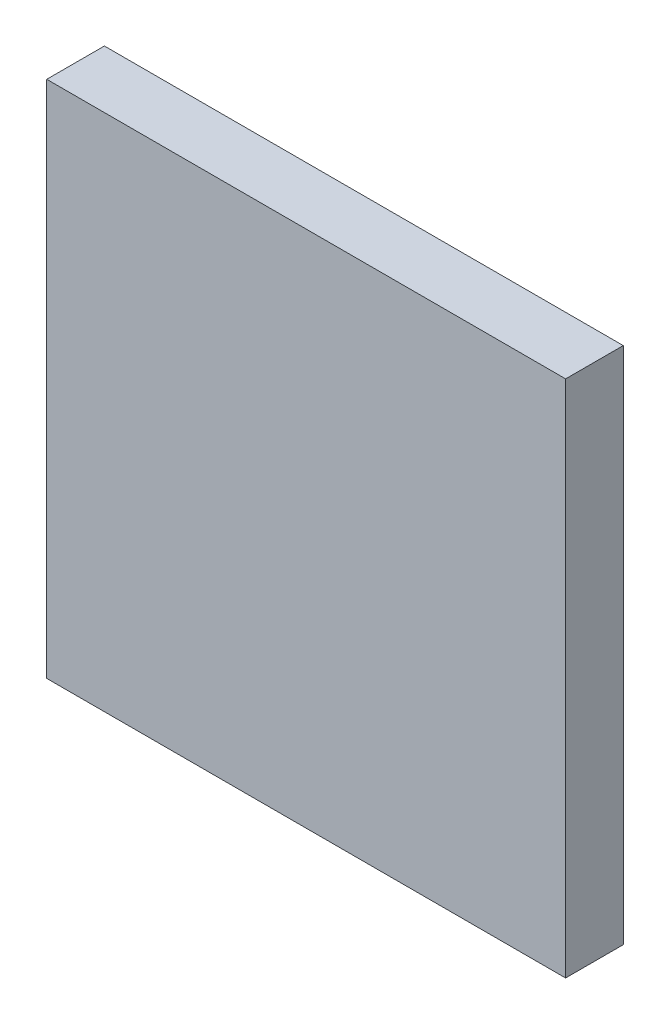
SolidWorks part; units mm, degrees
ref_plane "Спереди" through (0, 0, 0) normal (0, 0, 1) x (1, 0, 0)
ref_plane "Сверху" through (0, 0, 0) normal (0, 1, 0) x (1, 0, 0)
ref_plane "Справа" through (0, 0, 0) normal (1, 0, 0) x (0, 0, -1)
sketch "Эскиз1" plane through (0, 0, 0) normal (0, 0, 1) x (1, 0, 0)
  line L1 (-13.5, 13.5) -> (13.5, 13.5)
  line L2 (-13.5, 13.5) -> (-13.5, -13.5)
  line L3 (-13.5, -13.5) -> (13.5, -13.5)
  line L4 (13.5, 13.5) -> (13.5, -13.5)
  line L5 (-13.5, 13.5) -> (13.5, -13.5) construction
  line L6 (-13.5, -13.5) -> (13.5, 13.5) construction
  point P0 (0, 0)
  dimension "D1" = 27
  dimension "D2" = 27
extrude "Бобышка-Вытянуть1" add sketch "Эскиз1" along normal blind 3
sketch "Эскиз2" plane through (0, 0, 0) normal (0, 0, -1) x (-1, 0, 0)
  line L0 (0, 0) -> (13.5, 0) construction
  line L1 (13.5, 13.5) -> (13.5, -13.5) construction
  line L2 (0, 0) -> (0, -13.5) construction
  line L3 (13.5, -13.5) -> (-13.5, -13.5) construction
  line L4 (-0.5, -0.5) -> (-1.5, -0.5)
  line L5 (0.5, -1.5) -> (-0.5, -1.5)
  line L6 (0.5, -1.5) -> (0.5, -0.5)
  line L7 (0.5, 1.5) -> (-0.5, 1.5)
  line L8 (-0.5, -1.5) -> (-0.5, -0.5)
  line L9 (0.5, -1.5) -> (-0.5, 1.5) construction
  line L10 (0.5, 1.5) -> (-0.5, -1.5) construction
  line L11 (1.5, -0.5) -> (0.5, -0.5)
  line L12 (1.5, -0.5) -> (1.5, 0.5)
  line L13 (1.5, 0.5) -> (0.5, 0.5)
  line L14 (-1.5, -0.5) -> (-1.5, 0.5)
  line L15 (1.5, -0.5) -> (-1.5, 0.5) construction
  line L16 (1.5, 0.5) -> (-1.5, -0.5) construction
  line L17 (0.5, 0.5) -> (0.5, 1.5)
  line L18 (-0.5, 0.5) -> (-1.5, 0.5)
  line L19 (-0.5, 0.5) -> (-0.5, 1.5)
  line L20 (0, -9) -> (3.8771, -9) construction
  line L21 (1.5, 8.5) -> (-1.5, 9.5) construction
  line L22 (-0.5, -9.5) -> (-1.5, -9.5)
  line L23 (0.5, -10.5) -> (-0.5, -10.5)
  line L24 (0.5, -10.5) -> (0.5, -9.5)
  line L25 (0.5, -7.5) -> (-0.5, -7.5)
  line L26 (-0.5, -10.5) -> (-0.5, -9.5)
  line L27 (0.5, -10.5) -> (-0.5, -7.5) construction
  line L28 (0.5, -7.5) -> (-0.5, -10.5) construction
  line L29 (1.5, -9.5) -> (0.5, -9.5)
  line L30 (1.5, -9.5) -> (1.5, -8.5)
  line L31 (1.5, -8.5) -> (0.5, -8.5)
  line L32 (-1.5, -9.5) -> (-1.5, -8.5)
  line L33 (1.5, -9.5) -> (-1.5, -8.5) construction
  line L34 (1.5, -8.5) -> (-1.5, -9.5) construction
  line L35 (0.5, -8.5) -> (0.5, -7.5)
  line L36 (-0.5, -8.5) -> (-1.5, -8.5)
  line L37 (-0.5, -8.5) -> (-0.5, -7.5)
  line L38 (1.5, 9.5) -> (-1.5, 8.5) construction
  line L39 (0.5, 7.5) -> (-0.5, 10.5) construction
  line L40 (0.5, 10.5) -> (-0.5, 7.5) construction
  line L41 (-0.5, 8.5) -> (-0.5, 7.5)
  line L42 (-0.5, 8.5) -> (-1.5, 8.5)
  line L43 (0.5, 8.5) -> (0.5, 7.5)
  line L44 (-1.5, 9.5) -> (-1.5, 8.5)
  line L45 (1.5, 8.5) -> (0.5, 8.5)
  line L46 (1.5, 9.5) -> (1.5, 8.5)
  line L47 (1.5, 9.5) -> (0.5, 9.5)
  line L48 (-0.5, 10.5) -> (-0.5, 9.5)
  line L49 (0.5, 7.5) -> (-0.5, 7.5)
  line L50 (0.5, 10.5) -> (0.5, 9.5)
  line L51 (0.5, 10.5) -> (-0.5, 10.5)
  line L52 (-0.5, 9.5) -> (-1.5, 9.5)
  line L53 (2.5, -0.5) -> (5.5, -0.5)
  line L54 (5.5, -0.5) -> (5.5, -1.5)
  line L55 (5.5, -1.5) -> (6.5, -1.5)
  line L56 (6.5, -1.5) -> (6.5, -2.5)
  line L57 (6.5, -2.5) -> (7.5, -2.5)
  line L58 (7.5, -2.5) -> (7.5, -3.5)
  line L59 (7.5, -3.5) -> (8.5, -3.5)
  line L60 (8.5, -3.5) -> (8.5, -4.5)
  line L61 (8.5, -4.5) -> (5.5, -4.5)
  line L62 (5.5, -4.5) -> (5.5, -3.5)
  line L63 (5.5, -3.5) -> (4.5, -3.5)
  line L64 (4.5, -3.5) -> (4.5, -2.5)
  line L65 (4.5, -2.5) -> (3.5, -2.5)
  line L66 (3.5, -2.5) -> (3.5, -1.5)
  line L67 (3.5, -1.5) -> (2.5, -1.5)
  line L68 (2.5, -1.5) -> (2.5, -0.5)
  line L69 (5.5, -1.5) -> (5.5, -3.5) construction
  line L70 (5.5, -10.5) -> (5.5, -5.5)
  line L71 (5.5, -5.5) -> (10.5, -5.5)
  line L72 (10.5, -5.5) -> (10.5, -6.5)
  line L73 (10.5, -6.5) -> (6.5, -6.5)
  line L74 (6.5, -6.5) -> (6.5, -10.5)
  line L75 (6.5, -10.5) -> (5.5, -10.5)
  line L76 (5.5, -4.5) -> (5.5, -5.5) construction
  line L77 (8.5, -12.5) -> (7.5, -12.5)
  line L78 (7.5, -12.5) -> (7.5, -7.5)
  line L79 (7.5, -7.5) -> (12.5, -7.5)
  line L80 (12.5, -7.5) -> (12.5, -8.5)
  line L81 (12.5, -8.5) -> (8.5, -8.5)
  line L82 (8.5, -8.5) -> (8.5, -12.5)
  line L83 (9.5, -12.5) -> (9.5, -10.5)
  line L84 (9.5, -10.5) -> (10.5, -10.5)
  line L85 (10.5, -10.5) -> (10.5, -9.5)
  line L86 (10.5, -9.5) -> (12.5, -9.5)
  line L87 (12.5, -9.5) -> (12.5, -10.5)
  line L88 (12.5, -10.5) -> (11.5, -10.5)
  line L89 (11.5, -10.5) -> (11.5, -11.5)
  line L90 (11.5, -11.5) -> (10.5, -11.5)
  line L91 (10.5, -11.5) -> (10.5, -12.5)
  line L92 (10.5, -12.5) -> (9.5, -12.5)
  line L93 (0.5, -2.5) -> (0.5, -6.5)
  line L94 (0.5, -6.5) -> (1.5, -6.5)
  line L95 (1.5, -6.5) -> (1.5, -7.5)
  line L96 (1.5, -7.5) -> (2.5, -7.5)
  line L97 (2.5, -7.5) -> (2.5, -8.5)
  line L98 (2.5, -8.5) -> (3.5, -8.5)
  line L99 (3.5, -8.5) -> (3.5, -9.5)
  line L100 (3.5, -9.5) -> (4.5, -9.5)
  line L103 (4.5, -9.5) -> (4.5, -5.5)
  line L106 (4.5, -5.5) -> (3.5, -5.5)
  line L107 (3.5, -5.5) -> (3.5, -4.5)
  line L108 (3.5, -4.5) -> (2.5, -4.5)
  line L109 (2.5, -4.5) -> (2.5, -3.5)
  line L110 (2.5, -3.5) -> (1.5, -3.5)
  line L111 (1.5, -3.5) -> (1.5, -2.5)
  line L112 (1.5, -2.5) -> (0.5, -2.5)
  line L113 (0.5, -6.5) -> (0.5, -7.5) construction
  line L114 (1.5, -3.5) -> (1.5, -6.5) construction
  line L115 (2.5, -4.5) -> (2.5, -7.5) construction
  line L116 (0.5, -10.5) -> (0.5, -11.5) construction
  line L117 (4.5, -12.5) -> (0.5, -12.5)
  line L118 (4.5, -12.5) -> (4.5, -11.5)
  line L119 (4.5, -11.5) -> (0.5, -11.5)
  line L120 (0.5, -12.5) -> (0.5, -11.5)
  line L121 (9, 0) -> (17.8062, 0) construction
  line L122 (9, 0) -> (9, -6.8908) construction
  line L123 (8.5, -0.5) -> (7.5, -0.5)
  line L124 (9.5, -1.5) -> (8.5, -1.5)
  line L125 (9.5, -1.5) -> (9.5, -0.5)
  line L126 (9.5, 1.5) -> (8.5, 1.5)
  line L127 (8.5, -1.5) -> (8.5, -0.5)
  line L128 (9.5, -1.5) -> (8.5, 1.5) construction
  line L129 (9.5, 1.5) -> (8.5, -1.5) construction
  line L130 (10.5, -0.5) -> (9.5, -0.5)
  line L131 (10.5, -0.5) -> (10.5, 0.5)
  line L132 (10.5, 0.5) -> (9.5, 0.5)
  line L133 (7.5, -0.5) -> (7.5, 0.5)
  line L134 (10.5, -0.5) -> (7.5, 0.5) construction
  line L135 (10.5, 0.5) -> (7.5, -0.5) construction
  line L136 (9.5, 0.5) -> (9.5, 1.5)
  line L137 (8.5, 0.5) -> (7.5, 0.5)
  line L138 (8.5, 0.5) -> (8.5, 1.5)
  line L139 (-9, 0) -> (0, 0) construction
  line L140 (-9, 0) -> (-9, -7.0023) construction
  line L141 (-9.5, -0.5) -> (-10.5, -0.5)
  line L142 (-8.5, -1.5) -> (-9.5, -1.5)
  line L143 (-8.5, -1.5) -> (-8.5, -0.5)
  line L144 (-8.5, 1.5) -> (-9.5, 1.5)
  line L145 (-9.5, -1.5) -> (-9.5, -0.5)
  line L146 (-8.5, -1.5) -> (-9.5, 1.5) construction
  line L147 (-8.5, 1.5) -> (-9.5, -1.5) construction
  line L148 (-7.5, -0.5) -> (-8.5, -0.5)
  line L149 (-7.5, -0.5) -> (-7.5, 0.5)
  line L150 (-7.5, 0.5) -> (-8.5, 0.5)
  line L151 (-10.5, -0.5) -> (-10.5, 0.5)
  line L152 (-7.5, -0.5) -> (-10.5, 0.5) construction
  line L153 (-7.5, 0.5) -> (-10.5, -0.5) construction
  line L154 (-8.5, 0.5) -> (-8.5, 1.5)
  line L155 (-9.5, 0.5) -> (-10.5, 0.5)
  line L156 (-9.5, 0.5) -> (-9.5, 1.5)
  line L157 (-4.5, -11.5) -> (-0.5, -11.5)
  line L158 (-0.5, -12.5) -> (-0.5, -11.5)
  line L159 (-4.5, -12.5) -> (-0.5, -12.5)
  line L160 (-4.5, -12.5) -> (-4.5, -11.5)
  line L161 (-10.5, -12.5) -> (-9.5, -12.5)
  line L162 (-10.5, -11.5) -> (-10.5, -12.5)
  line L163 (-11.5, -11.5) -> (-10.5, -11.5)
  line L164 (-11.5, -10.5) -> (-11.5, -11.5)
  line L165 (-12.5, -10.5) -> (-11.5, -10.5)
  line L166 (-12.5, -9.5) -> (-12.5, -10.5)
  line L167 (-10.5, -9.5) -> (-12.5, -9.5)
  line L168 (-10.5, -10.5) -> (-10.5, -9.5)
  line L169 (-9.5, -10.5) -> (-10.5, -10.5)
  line L170 (-9.5, -12.5) -> (-9.5, -10.5)
  line L171 (-12.5, -8.5) -> (-8.5, -8.5)
  line L172 (-12.5, -7.5) -> (-12.5, -8.5)
  line L173 (-7.5, -7.5) -> (-12.5, -7.5)
  line L174 (-7.5, -12.5) -> (-7.5, -7.5)
  line L175 (-8.5, -12.5) -> (-7.5, -12.5)
  line L176 (-8.5, -8.5) -> (-8.5, -12.5)
  line L177 (-6.5, -6.5) -> (-6.5, -10.5)
  line L178 (-10.5, -6.5) -> (-6.5, -6.5)
  line L179 (-10.5, -5.5) -> (-10.5, -6.5)
  line L180 (-5.5, -5.5) -> (-10.5, -5.5)
  line L181 (-5.5, -10.5) -> (-5.5, -5.5)
  line L182 (-6.5, -10.5) -> (-5.5, -10.5)
  line L183 (-3.5, -1.5) -> (-2.5, -1.5)
  line L184 (-3.5, -2.5) -> (-3.5, -1.5)
  line L185 (-4.5, -2.5) -> (-3.5, -2.5)
  line L186 (-4.5, -3.5) -> (-4.5, -2.5)
  line L187 (-5.5, -3.5) -> (-4.5, -3.5)
  line L188 (-5.5, -4.5) -> (-5.5, -3.5)
  line L189 (-8.5, -4.5) -> (-5.5, -4.5)
  line L190 (-8.5, -3.5) -> (-8.5, -4.5)
  line L191 (-7.5, -3.5) -> (-8.5, -3.5)
  line L192 (-7.5, -2.5) -> (-7.5, -3.5)
  line L193 (-6.5, -2.5) -> (-7.5, -2.5)
  line L194 (-6.5, -1.5) -> (-6.5, -2.5)
  line L195 (-5.5, -1.5) -> (-6.5, -1.5)
  line L196 (-5.5, -0.5) -> (-5.5, -1.5)
  line L197 (-2.5, -0.5) -> (-5.5, -0.5)
  line L198 (-2.5, -1.5) -> (-2.5, -0.5)
  line L199 (-3.5, -9.5) -> (-4.5, -9.5)
  line L200 (-3.5, -8.5) -> (-3.5, -9.5)
  line L201 (-2.5, -8.5) -> (-3.5, -8.5)
  line L202 (-2.5, -7.5) -> (-2.5, -8.5)
  line L203 (-1.5, -7.5) -> (-2.5, -7.5)
  line L204 (-1.5, -6.5) -> (-1.5, -7.5)
  line L205 (-0.5, -6.5) -> (-1.5, -6.5)
  line L206 (-0.5, -2.5) -> (-0.5, -6.5)
  line L207 (-1.5, -2.5) -> (-0.5, -2.5)
  line L208 (-1.5, -3.5) -> (-1.5, -2.5)
  line L209 (-2.5, -3.5) -> (-1.5, -3.5)
  line L210 (-2.5, -4.5) -> (-2.5, -3.5)
  line L211 (-3.5, -4.5) -> (-2.5, -4.5)
  line L212 (-3.5, -5.5) -> (-3.5, -4.5)
  line L213 (-4.5, -5.5) -> (-3.5, -5.5)
  line L214 (-4.5, -9.5) -> (-4.5, -5.5)
  line L215 (8.5, -4.5) -> (11.5, -4.5) construction
  line L216 (12.5, -0.5) -> (11.5, -0.5)
  line L217 (12.5, -0.5) -> (12.5, -4.5)
  line L218 (12.5, -4.5) -> (11.5, -4.5)
  line L219 (11.5, -0.5) -> (11.5, -4.5)
  line L220 (12.5, -4.5) -> (12.5, -7.5) construction
  line L221 (-12.5, -4.5) -> (-11.5, -4.5)
  line L222 (-11.5, -0.5) -> (-11.5, -4.5)
  line L223 (-12.5, -0.5) -> (-11.5, -0.5)
  line L224 (-12.5, -0.5) -> (-12.5, -4.5)
  line L225 (-10.5, 11.5) -> (-10.5, 12.5)
  line L226 (-11.5, 11.5) -> (-10.5, 11.5)
  line L227 (-11.5, 10.5) -> (-11.5, 11.5)
  line L228 (-12.5, 10.5) -> (-11.5, 10.5)
  line L229 (-12.5, 9.5) -> (-12.5, 10.5)
  line L230 (-10.5, 9.5) -> (-12.5, 9.5)
  line L231 (-10.5, 10.5) -> (-10.5, 9.5)
  line L232 (-9.5, 10.5) -> (-10.5, 10.5)
  line L233 (-9.5, 12.5) -> (-9.5, 10.5)
  line L234 (-10.5, 12.5) -> (-9.5, 12.5)
  line L235 (-12.5, 7.5) -> (-12.5, 8.5)
  line L236 (-7.5, 7.5) -> (-12.5, 7.5)
  line L237 (-7.5, 12.5) -> (-7.5, 7.5)
  line L238 (-8.5, 12.5) -> (-7.5, 12.5)
  line L239 (-8.5, 8.5) -> (-8.5, 12.5)
  line L240 (-12.5, 8.5) -> (-8.5, 8.5)
  line L241 (-10.5, 6.5) -> (-6.5, 6.5)
  line L242 (-10.5, 5.5) -> (-10.5, 6.5)
  line L243 (-5.5, 5.5) -> (-10.5, 5.5)
  line L244 (-5.5, 10.5) -> (-5.5, 5.5)
  line L245 (-6.5, 10.5) -> (-5.5, 10.5)
  line L246 (-6.5, 6.5) -> (-6.5, 10.5)
  line L247 (-12.5, 0.5) -> (-12.5, 4.5)
  line L248 (-12.5, 0.5) -> (-11.5, 0.5)
  line L249 (-11.5, 0.5) -> (-11.5, 4.5)
  line L250 (-12.5, 4.5) -> (-11.5, 4.5)
  line L251 (-3.5, 2.5) -> (-3.5, 1.5)
  line L252 (-4.5, 2.5) -> (-3.5, 2.5)
  line L253 (-4.5, 3.5) -> (-4.5, 2.5)
  line L254 (-5.5, 3.5) -> (-4.5, 3.5)
  line L255 (-5.5, 4.5) -> (-5.5, 3.5)
  line L256 (-8.5, 4.5) -> (-5.5, 4.5)
  line L257 (-8.5, 3.5) -> (-8.5, 4.5)
  line L258 (-7.5, 3.5) -> (-8.5, 3.5)
  line L259 (-7.5, 2.5) -> (-7.5, 3.5)
  line L260 (-6.5, 2.5) -> (-7.5, 2.5)
  line L261 (-6.5, 1.5) -> (-6.5, 2.5)
  line L262 (-5.5, 1.5) -> (-6.5, 1.5)
  line L263 (-5.5, 0.5) -> (-5.5, 1.5)
  line L264 (-2.5, 0.5) -> (-5.5, 0.5)
  line L265 (-2.5, 1.5) -> (-2.5, 0.5)
  line L266 (-3.5, 1.5) -> (-2.5, 1.5)
  line L267 (-3.5, 8.5) -> (-3.5, 9.5)
  line L268 (-2.5, 8.5) -> (-3.5, 8.5)
  line L269 (-2.5, 7.5) -> (-2.5, 8.5)
  line L270 (-1.5, 7.5) -> (-2.5, 7.5)
  line L271 (-1.5, 6.5) -> (-1.5, 7.5)
  line L272 (-0.5, 6.5) -> (-1.5, 6.5)
  line L273 (-0.5, 2.5) -> (-0.5, 6.5)
  line L274 (-1.5, 2.5) -> (-0.5, 2.5)
  line L275 (-1.5, 3.5) -> (-1.5, 2.5)
  line L276 (-2.5, 3.5) -> (-1.5, 3.5)
  line L277 (-2.5, 4.5) -> (-2.5, 3.5)
  line L278 (-3.5, 4.5) -> (-2.5, 4.5)
  line L279 (-3.5, 5.5) -> (-3.5, 4.5)
  line L280 (-4.5, 5.5) -> (-3.5, 5.5)
  line L281 (-4.5, 9.5) -> (-4.5, 5.5)
  line L282 (-3.5, 9.5) -> (-4.5, 9.5)
  line L283 (-4.5, 12.5) -> (-4.5, 11.5)
  line L284 (-4.5, 12.5) -> (-0.5, 12.5)
  line L285 (-0.5, 12.5) -> (-0.5, 11.5)
  line L286 (-4.5, 11.5) -> (-0.5, 11.5)
  line L287 (4.5, 11.5) -> (0.5, 11.5)
  line L288 (0.5, 12.5) -> (0.5, 11.5)
  line L289 (4.5, 12.5) -> (0.5, 12.5)
  line L290 (4.5, 12.5) -> (4.5, 11.5)
  line L291 (3.5, 9.5) -> (4.5, 9.5)
  line L292 (3.5, 8.5) -> (3.5, 9.5)
  line L293 (2.5, 8.5) -> (3.5, 8.5)
  line L294 (2.5, 7.5) -> (2.5, 8.5)
  line L295 (1.5, 7.5) -> (2.5, 7.5)
  line L296 (1.5, 6.5) -> (1.5, 7.5)
  line L297 (0.5, 6.5) -> (1.5, 6.5)
  line L298 (0.5, 2.5) -> (0.5, 6.5)
  line L299 (1.5, 2.5) -> (0.5, 2.5)
  line L300 (1.5, 3.5) -> (1.5, 2.5)
  line L301 (2.5, 3.5) -> (1.5, 3.5)
  line L302 (2.5, 4.5) -> (2.5, 3.5)
  line L303 (3.5, 4.5) -> (2.5, 4.5)
  line L304 (3.5, 5.5) -> (3.5, 4.5)
  line L305 (4.5, 5.5) -> (3.5, 5.5)
  line L306 (4.5, 9.5) -> (4.5, 5.5)
  line L307 (10.5, 12.5) -> (9.5, 12.5)
  line L308 (10.5, 11.5) -> (10.5, 12.5)
  line L309 (11.5, 11.5) -> (10.5, 11.5)
  line L310 (11.5, 10.5) -> (11.5, 11.5)
  line L311 (12.5, 10.5) -> (11.5, 10.5)
  line L312 (12.5, 9.5) -> (12.5, 10.5)
  line L313 (10.5, 9.5) -> (12.5, 9.5)
  line L314 (10.5, 10.5) -> (10.5, 9.5)
  line L315 (9.5, 10.5) -> (10.5, 10.5)
  line L316 (9.5, 12.5) -> (9.5, 10.5)
  line L317 (12.5, 8.5) -> (8.5, 8.5)
  line L318 (12.5, 7.5) -> (12.5, 8.5)
  line L319 (7.5, 7.5) -> (12.5, 7.5)
  line L320 (7.5, 12.5) -> (7.5, 7.5)
  line L321 (8.5, 12.5) -> (7.5, 12.5)
  line L322 (8.5, 8.5) -> (8.5, 12.5)
  line L323 (6.5, 6.5) -> (6.5, 10.5)
  line L324 (10.5, 6.5) -> (6.5, 6.5)
  line L325 (10.5, 5.5) -> (10.5, 6.5)
  line L326 (5.5, 5.5) -> (10.5, 5.5)
  line L327 (5.5, 10.5) -> (5.5, 5.5)
  line L328 (6.5, 10.5) -> (5.5, 10.5)
  line L329 (3.5, 1.5) -> (2.5, 1.5)
  line L330 (3.5, 2.5) -> (3.5, 1.5)
  line L331 (4.5, 2.5) -> (3.5, 2.5)
  line L332 (4.5, 3.5) -> (4.5, 2.5)
  line L333 (5.5, 3.5) -> (4.5, 3.5)
  line L334 (5.5, 4.5) -> (5.5, 3.5)
  line L335 (8.5, 4.5) -> (5.5, 4.5)
  line L336 (8.5, 3.5) -> (8.5, 4.5)
  line L337 (7.5, 3.5) -> (8.5, 3.5)
  line L338 (7.5, 2.5) -> (7.5, 3.5)
  line L339 (6.5, 2.5) -> (7.5, 2.5)
  line L340 (6.5, 1.5) -> (6.5, 2.5)
  line L341 (5.5, 1.5) -> (6.5, 1.5)
  line L342 (5.5, 0.5) -> (5.5, 1.5)
  line L343 (2.5, 0.5) -> (5.5, 0.5)
  line L344 (2.5, 1.5) -> (2.5, 0.5)
  line L345 (12.5, 4.5) -> (11.5, 4.5)
  line L346 (11.5, 0.5) -> (11.5, 4.5)
  line L347 (12.5, 0.5) -> (11.5, 0.5)
  line L348 (12.5, 0.5) -> (12.5, 4.5)
  point P65 (5.5, -1.5)
  dimension "D1" = 3
  dimension "D2" = 3
  dimension "D3" = 1
  dimension "D4" = 1
  dimension "D5" = 3
  dimension "D6" = 3
  dimension "D7" = 1
  dimension "D8" = 1
  dimension "D9" = 9
  dimension "D10" = 1
  dimension "D11" = 1
  dimension "D12" = 1
  dimension "D13" = 1
  dimension "D14" = 1
  dimension "D15" = 1
  dimension "D16" = 1
  dimension "D17" = 1
  dimension "D18" = 1
  dimension "D19" = 1
  dimension "D20" = 1
  dimension "D21" = 1
  dimension "D22" = 1
  dimension "D23" = 0.5
  dimension "D24" = 1
  dimension "D25" = 1
  dimension "D26" = 1
  dimension "D27" = 5
  dimension "D28" = 5
  dimension "D29" = 1
  dimension "D30" = 5
  dimension "D31" = 5
  dimension "D32" = 1
  dimension "D33" = 1
  dimension "D34" = 1
  dimension "D35" = 1
  dimension "D36" = 2
  dimension "D37" = 1
  dimension "D38" = 1
  dimension "D39" = 1
  dimension "D40" = 1
  dimension "D41" = 1
  dimension "D42" = 1
  dimension "D43" = 1
  dimension "D44" = 1
  dimension "D45" = 1
  dimension "D46" = 1
  dimension "D47" = 1
  dimension "D48" = 1
  dimension "D49" = 1
  dimension "D50" = 1
  dimension "D51" = 1
  dimension "D52" = 1
  dimension "D53" = 1
  dimension "D54" = 4
  dimension "D55" = 4
  dimension "D56" = 1
  dimension "D57" = 1
  dimension "D58" = 1
  dimension "D59" = 1
  dimension "D60" = 1
  dimension "D61" = 1
  dimension "D62" = 3
  dimension "D63" = 3
  dimension "D64" = 1
  dimension "D65" = 1
  dimension "D66" = 3
  dimension "D67" = 3
  dimension "D68" = 1
  dimension "D69" = 1
  dimension "D70" = 9
  dimension "D71" = 9
  dimension "D72" = 1
  dimension "D73" = 4
extrude "Вырез-Вытянуть1" cut sketch "Эскиз2" against normal blind 2
